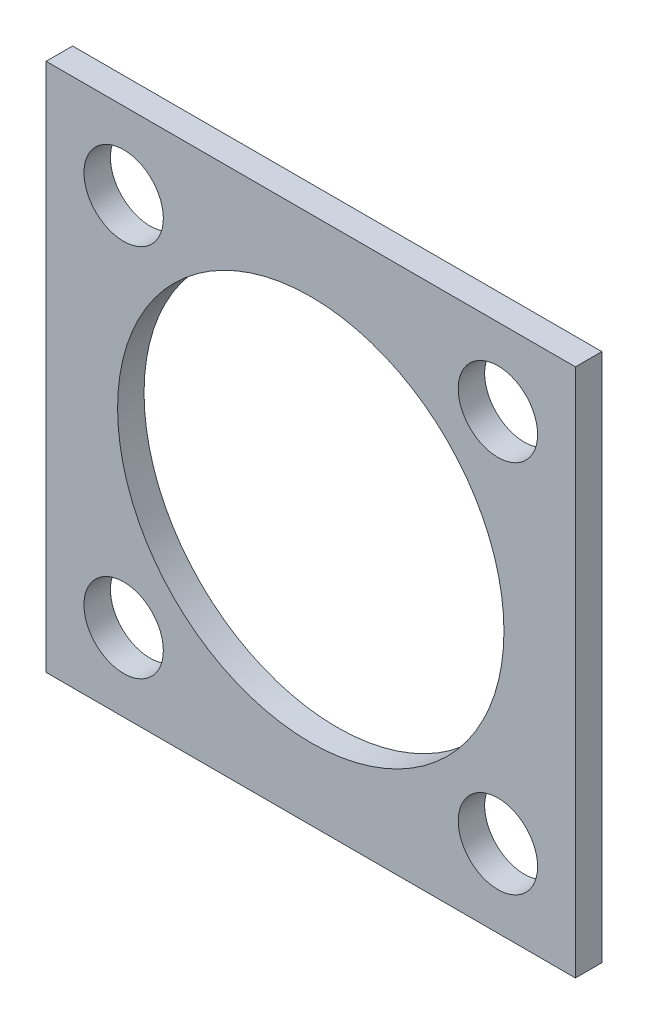
SolidWorks part; units mm, degrees
ref_plane "Front Plane" through (0, 0, 0) normal (0, 0, 1) x (1, 0, 0)
ref_plane "Top Plane" through (0, 0, 0) normal (0, 1, 0) x (1, 0, 0)
ref_plane "Right Plane" through (0, 0, 0) normal (1, 0, 0) x (0, 0, -1)
sketch "Sketch1" plane through (0, 0, 0) normal (0, 0, 1) x (1, 0, 0)
  line L1 (10, -10) -> (-10, -10)
  line L2 (10, -10) -> (10, 10)
  line L3 (10, 10) -> (-10, 10)
  line L4 (-10, -10) -> (-10, 10)
  line L5 (10, -10) -> (-10, 10) construction
  line L6 (10, 10) -> (-10, -10) construction
  circle A0 centre (0, 0) radius 7.3
  point P0 (0, 0)
  dimension "D2" = 14.6
  dimension "D1" = 20
extrude "Boss-Extrude1" add sketch "Sketch1" along normal blind 1
sketch "Sketch2" plane through (0, 0, 1) normal (0, 0, 1) x (1, 0, 0)
  line L0 (-7.0711, -7.0711) -> (7.0711, 7.0711) construction
  line L1 (-7.0711, 7.0711) -> (7.0711, -7.0711) construction
  circle A0 centre (-7.0711, 7.0711) radius 1.5
  circle A1 centre (7.0711, 7.0711) radius 1.5
  circle A2 centre (7.0711, -7.0711) radius 1.5
  circle A3 centre (-7.0711, -7.0711) radius 1.5
  dimension "D1" = 3
  dimension "D2" = 10
extrude "Cut-Extrude1" cut sketch "Sketch2" against normal blind 1 contours A0 | A1 | A2 | A3
